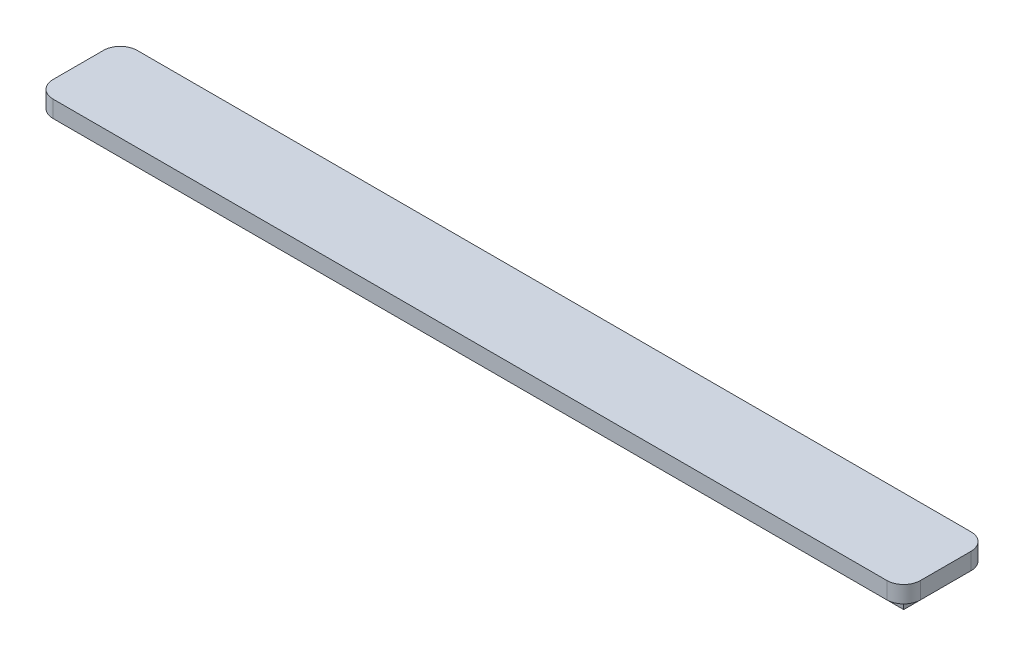
SolidWorks part; units mm, degrees
ref_plane "Front Plane" through (0, 0, 0) normal (0, 0, 1) x (1, 0, 0)
ref_plane "Top Plane" through (0, 0, 0) normal (0, 1, 0) x (1, 0, 0)
ref_plane "Right Plane" through (0, 0, 0) normal (1, 0, 0) x (0, 0, -1)
sketch "Sketch1" plane through (0, 0, 0) normal (0, 1, 0) x (1, 0, 0)
  line L1 (-49.5, 3) -> (49.5, 3)
  line L2 (-49.5, 3) -> (-49.5, -3)
  line L3 (-49.5, -3) -> (49.5, -3)
  line L4 (49.5, 3) -> (49.5, -3)
  line L5 (-49.5, 3) -> (49.5, -3) construction
  line L6 (-49.5, -3) -> (49.5, 3) construction
  point P0 (0, 0)
  dimension "D1" = 99
  dimension "D2" = 6
extrude "Boss-Extrude1" add sketch "Sketch1" along normal blind 2
sketch "Sketch2" plane through (0, 2, 0) normal (0, 1, 0) x (1, 0, 0)
  line L0 (50.5, -4) -> (50.5, 4)
  line L1 (50.5, 4) -> (-50.5, 4)
  line L2 (-50.5, 4) -> (-50.5, -4)
  line L3 (-50.5, -4) -> (50.5, -4)
  line L4 (49.5, -3) -> (49.5, 3)
  line L5 (49.5, 3) -> (-49.5, 3)
  line L6 (-49.5, 3) -> (-49.5, -3)
  line L7 (-49.5, -3) -> (49.5, -3)
  line L8 (49.5, -3) -> (49.5, 3) construction
  line L9 (49.5, 3) -> (-49.5, 3) construction
  line L10 (-49.5, 3) -> (-49.5, -3) construction
  line L11 (-49.5, -3) -> (49.5, -3) construction
  dimension "D1" = 0
  dimension "D2" = 1
extrude "Boss-Extrude3" add sketch "Sketch2" along normal blind 2 separate body
draft "Draft1" type of draft neutral plane draft angle 10 faces to draft 4 face at (49.5, 1, 0) face at (0, 1, 3) face at (-49.5, 1, 0) face at (0, 1, -3) neutral plane through (0, 0, 0) neutral plane normal (0, -1, 0) parameters "D1"=10
sketch "Sketch3" plane through (0, 4, 0) normal (0, 1, 0) x (1, 0, 0)
  line L0 (-51.5, -5) -> (51.5, -5)
  line L1 (51.5, -5) -> (51.5, 5)
  line L2 (51.5, 5) -> (-51.5, 5)
  line L3 (-51.5, 5) -> (-51.5, -5)
  line L4 (-50.5, -4) -> (50.5, -4)
  line L5 (50.5, -4) -> (50.5, 4)
  line L6 (50.5, 4) -> (-50.5, 4)
  line L7 (-50.5, 4) -> (-50.5, -4)
  line L8 (-50.5, -4) -> (50.5, -4)
  line L9 (50.5, -4) -> (50.5, 4)
  line L10 (50.5, 4) -> (-50.5, 4)
  line L11 (-50.5, 4) -> (-50.5, -4)
  dimension "D1" = 0
  dimension "D2" = 1
extrude "Boss-Extrude4" add sketch "Sketch3" against normal blind 2
fillet "Fillet1" radius 2 4 edges at (-51.5, 3, -5) (51.5, 3, -5) (51.5, 3, 5) (-51.5, 3, 5)
